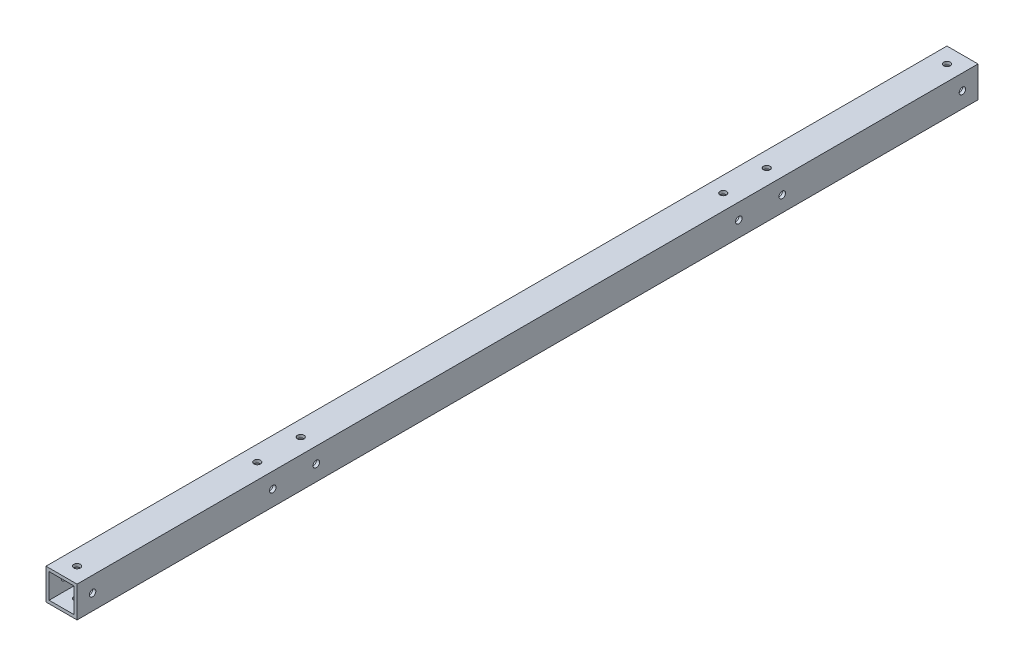
SolidWorks part; units mm, degrees
ref_plane "前视基准面" through (0, 0, 0) normal (0, 0, 1) x (1, 0, 0)
ref_plane "上视基准面" through (0, 0, 0) normal (0, 1, 0) x (1, 0, 0)
ref_plane "右视基准面" through (0, 0, 0) normal (1, 0, 0) x (0, 0, -1)
other "Configuration Table"
sketch "草图1" plane through (0, 0, 0) normal (0, 0, 1) x (1, 0, 0)
  line L1 (-10, -10) -> (10, -10)
  line L2 (-10, -10) -> (-10, 10)
  line L3 (-10, 10) -> (10, 10)
  line L4 (10, -10) -> (10, 10)
  line L5 (-10, -10) -> (10, 10) construction
  line L6 (-10, 10) -> (10, -10) construction
  line L7 (-8, -8) -> (8, -8)
  line L8 (-8, -8) -> (-8, 8)
  line L9 (-8, 8) -> (8, 8)
  line L10 (8, -8) -> (8, 8)
  line L11 (-8, -8) -> (8, 8) construction
  line L12 (-8, 8) -> (8, -8) construction
  point P0 (0, 0)
  point P6 (0, 0)
  dimension "D1" = 20
  dimension "D2" = 2
extrude "凸台-拉伸1" add sketch "草图1" along normal blind 580 contours L1 L4 L3 L2 L10 L7 L8 L9
sketch "草图2" plane through (0, 10, 0) normal (0, 1, 0) x (1, 0, 0)
  line L0 (0, 0) -> (0, -119.3181) construction
  line L1 (-10, 0) -> (10, 0) construction
  circle A0 centre (0, -10) radius 2.1
  circle A1 centre (0, -126) radius 2.1
  circle A2 centre (0, -154) radius 2.1
  dimension "D1" = 4.2
  dimension "D3" = 4.2
  dimension "D6" = 4.2
  dimension "D2" = 10
  dimension "D4" = 126
  dimension "D5" = 28
extrude "切除-拉伸1" cut sketch "草图2" against normal blind 20
ref_plane "基准面1" through (0, 0, 290) normal (0, 0, 1) x (1, 0, 0)
mirror "镜向1" about plane through (0, 0, 290) normal (0, 0, 1) of "切除-拉伸1"
sketch "草图3" plane through (10, 0, 0) normal (1, 0, 0) x (0, 0, -1)
  line L0 (-580, -10) -> (-580, 10) construction
  line L1 (-580, -10) -> (0, -10) construction
  line L2 (-580, 0) -> (0, 0) construction
  line L4 (0, -10) -> (0, 10) construction
  line L5 (-580, 10) -> (0, 10) construction
  line L6 (-290, 11) -> (-290, -11) construction
  circle A0 centre (-570, 0) radius 2.1
  circle A1 centre (-10, 0) radius 2.1
  circle A2 centre (-454, 0) radius 2.1
  circle A3 centre (-426, 0) radius 2.1
  circle A4 centre (-126, 0) radius 2.1
  circle A5 centre (-154, 0) radius 2.1
  dimension "D1" = 4.2
  dimension "D4" = 4.2
  dimension "D8" = 4.2
  dimension "D10" = 4.2
  dimension "D2" = 10
  dimension "D3" = 10
  dimension "D5" = 10
  dimension "D6" = 10
  dimension "D7" = 126
  dimension "D9" = 28
extrude "切除-拉伸2" cut sketch "草图3" against normal through all
